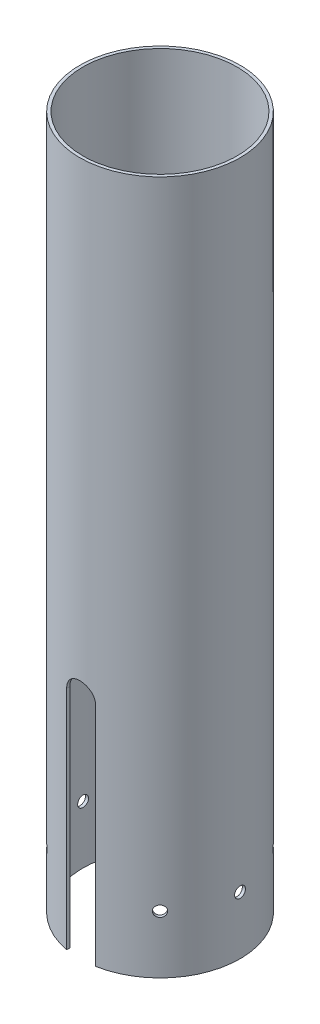
SolidWorks part; units mm, degrees
material "Corrugated Paper"
ref_plane "Front Plane" through (0, 0, 0) normal (0, 0, 1) x (1, 0, 0)
ref_plane "Top Plane" through (0, 0, 0) normal (0, 1, 0) x (1, 0, 0)
ref_plane "Right Plane" through (0, 0, 0) normal (1, 0, 0) x (0, 0, -1)
sketch "Sketch1" plane through (0, 0, 0) normal (0, 1, 0) x (1, 0, 0)
  circle A0 centre (0, 0) radius 52.832
  circle A1 centre (0, 0) radius 50.8
  dimension "D1" = 105.664
  dimension "D2" = 101.6
extrude "Boss-Extrude1" add sketch "Sketch1" along normal blind 457.2
sketch "Sketch2" plane through (0, 0, 0) normal (0, 0, 1) x (1, 0, 0)
  line L0 (0, 158.75) -> (0, 0) construction
  line L1 (-9.525, 149.225) -> (-9.525, 0)
  line L2 (-52.832, 0) -> (52.832, 0) construction
  line L3 (9.525, 149.225) -> (9.525, 0)
  line L4 (9.525, 0) -> (-9.525, 0)
  arc A0 (9.525, 149.225) -> (-9.525, 149.225) centre (0, 149.225) ccw
  dimension "D2" = 19.05
  dimension "D1" = 158.75
extrude "Cut-Extrude1" cut sketch "Sketch2" along normal through all
ref_plane "Plane1" through (0, 0, -52.832) normal (0, 0, -1) x (-1, 0, 0)
hole_wizard "1/4 Clearance Hole1" positions "Sketch3" profile "Sketch4" hole size "1/4" standard "ANSI Inch"
sketch "Sketch3" plane through (0, 0, -52.832) normal (0, 0, -1) x (-1, 0, 0)
  point P0 (0, 38.1)
  dimension "D1" = 38.1
sketch "Sketch4" plane through (0, 38.1, -52.832) normal (1, 0, 0) x (0, 1, 0)
  line L0 (0, 0) -> (0, 12.8138)
  line L1 (0, 12.8138) -> (3.5712, 10.668)
  line L2 (3.5712, 10.668) -> (3.5712, 0)
  line L5 (3.5712, 0) -> (0, 0)
  line L10 (0, 12.8138) -> (-3.5712, 10.668) construction
  line L11 (0, -6.35) -> (0, 107.95) construction
  dimension "Hole Dia." = 7.1425
  dimension "Hole Depth" = 10.668
  dimension "Drill Angle" = 118
pattern_circular "CirPattern1" count 8 over 360 about axis through (0, 457.2, 0) along (0, -1, 0) skipping 4 of "1/4 Clearance Hole1"
